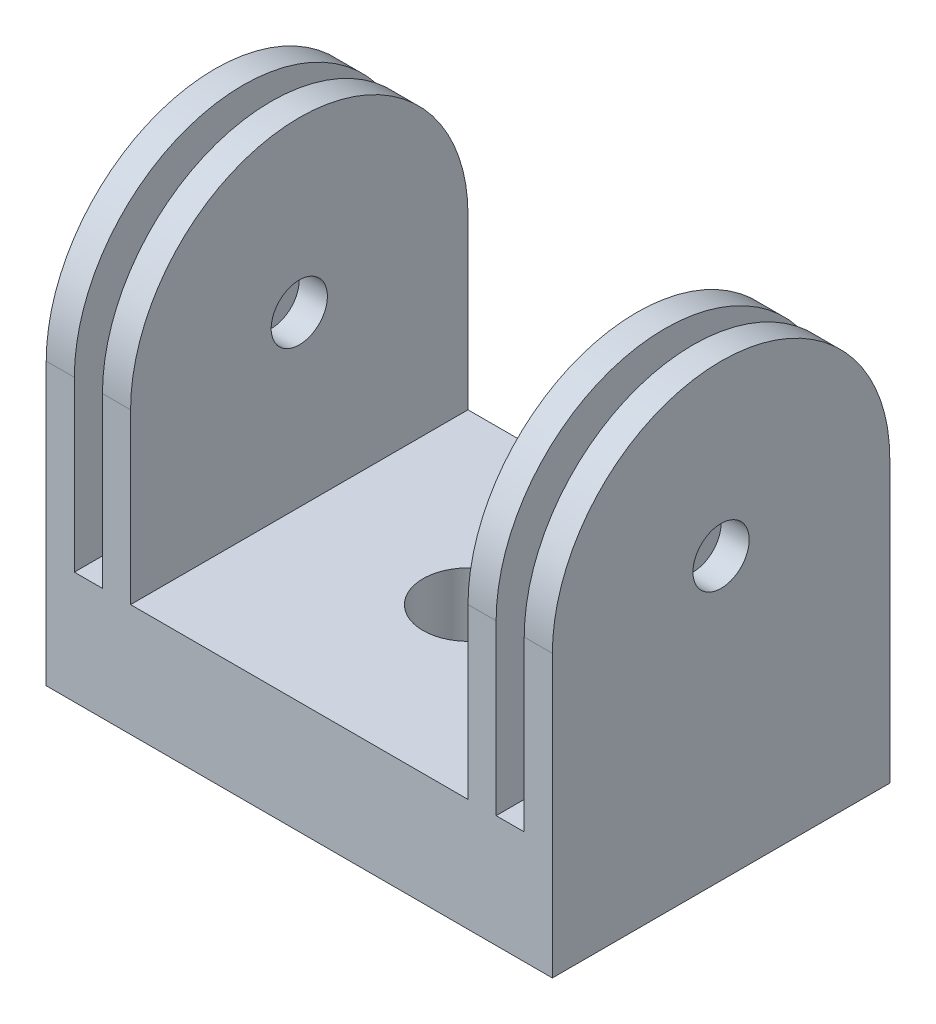
SolidWorks part; units mm, degrees
material "6061 Alloy"
ref_plane "Front Plane" through (0, 0, 0) normal (0, 0, 1) x (1, 0, 0)
ref_plane "Top Plane" through (0, 0, 0) normal (0, 1, 0) x (1, 0, 0)
ref_plane "Right Plane" through (0, 0, 0) normal (1, 0, 0) x (0, 0, -1)
sketch "Sketch1" plane through (0, 0, 0) normal (0, 1, 0) x (1, 0, 0)
  line L1 (-22.5, 15) -> (22.5, 15)
  line L2 (-22.5, 15) -> (-22.5, -15)
  line L3 (-22.5, -15) -> (22.5, -15)
  line L4 (22.5, 15) -> (22.5, -15)
  line L5 (0, -15) -> (0, 15) construction
  line L6 (-22.5, 0) -> (22.5, 0) construction
  circle A0 centre (0, 0) radius 4
  point P0 (0, 0)
  dimension "D1" = 45
  dimension "D3" = 8
  dimension "D2" = 30
extrude "Boss-Extrude1" add sketch "Sketch1" along normal blind 10 contours L4 L1 L2 L3 A0
sketch "Sketch2" plane through (22.5, 0, 0) normal (1, 0, 0) x (0, 0, -1)
  line L0 (15, 10) -> (15, 0) construction
  line L1 (-15, 10) -> (15, 10)
  line L2 (-15, 10) -> (-15, 25)
  line L4 (15, 10) -> (15, 25)
  arc A0 (-15, 25) -> (15, 25) centre (0, 25) cw
  circle A1 centre (0, 25) radius 2.5
  dimension "D2" = 5
  dimension "D4" = 15
  dimension "D1" = 15
  dimension "D3" = 10
extrude "Boss-Extrude2" add sketch "Sketch2" against normal blind 2.5
ref_plane "Plane1" through (18.75, 0, 0) normal (1, 0, 0) x (0, 0, -1)
mirror "Mirror2" about plane through (18.75, 0, 0) normal (1, 0, 0) of "Boss-Extrude2"
mirror "Mirror3" about plane through (0, 0, 0) normal (1, 0, 0) of "Mirror2", "Boss-Extrude2"
